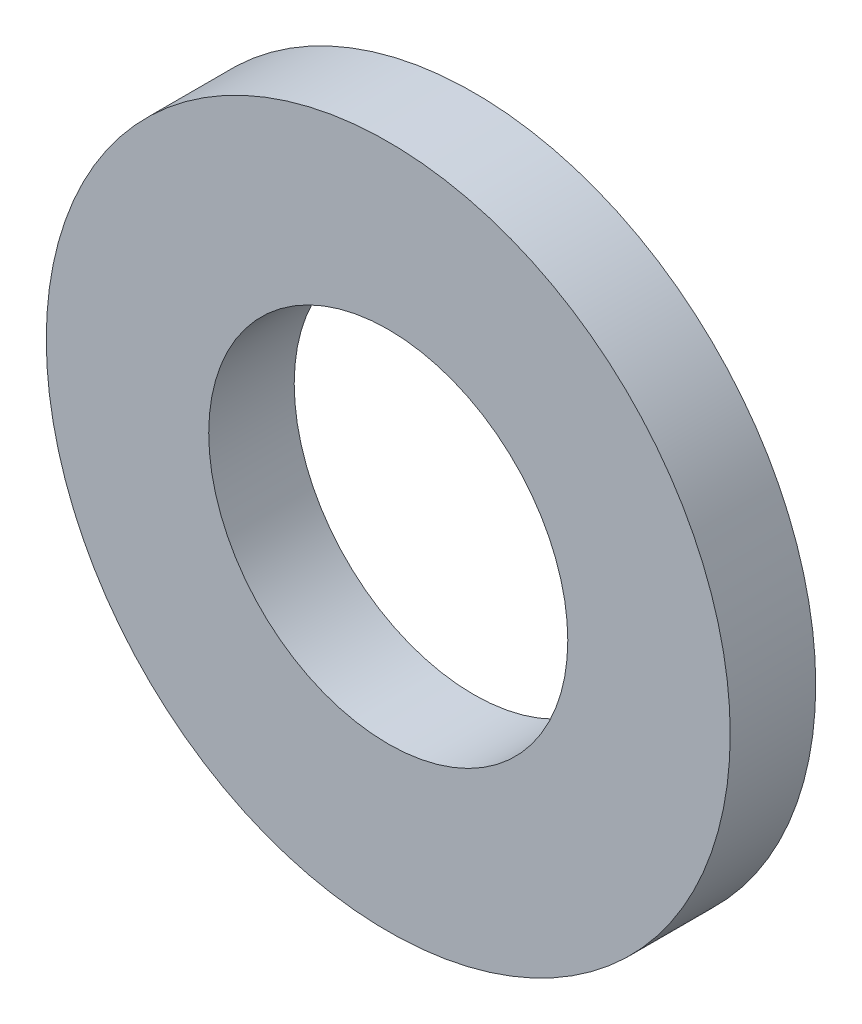
SolidWorks part; units mm, degrees
ref_plane "Front Plane" through (0, 0, 0) normal (0, 0, 1) x (1, 0, 0)
ref_plane "Top Plane" through (0, 0, 0) normal (0, 1, 0) x (1, 0, 0)
ref_plane "Right Plane" through (0, 0, 0) normal (1, 0, 0) x (0, 0, -1)
sketch "Sketch1" plane through (0, 0, 0) normal (0, 0, 1) x (1, 0, 0)
  circle A0 centre (0, 0) radius 2
  circle A1 centre (0, 0) radius 1.05
extrude "Ring_Envelope" add sketch "Sketch1" along normal blind 0.5
